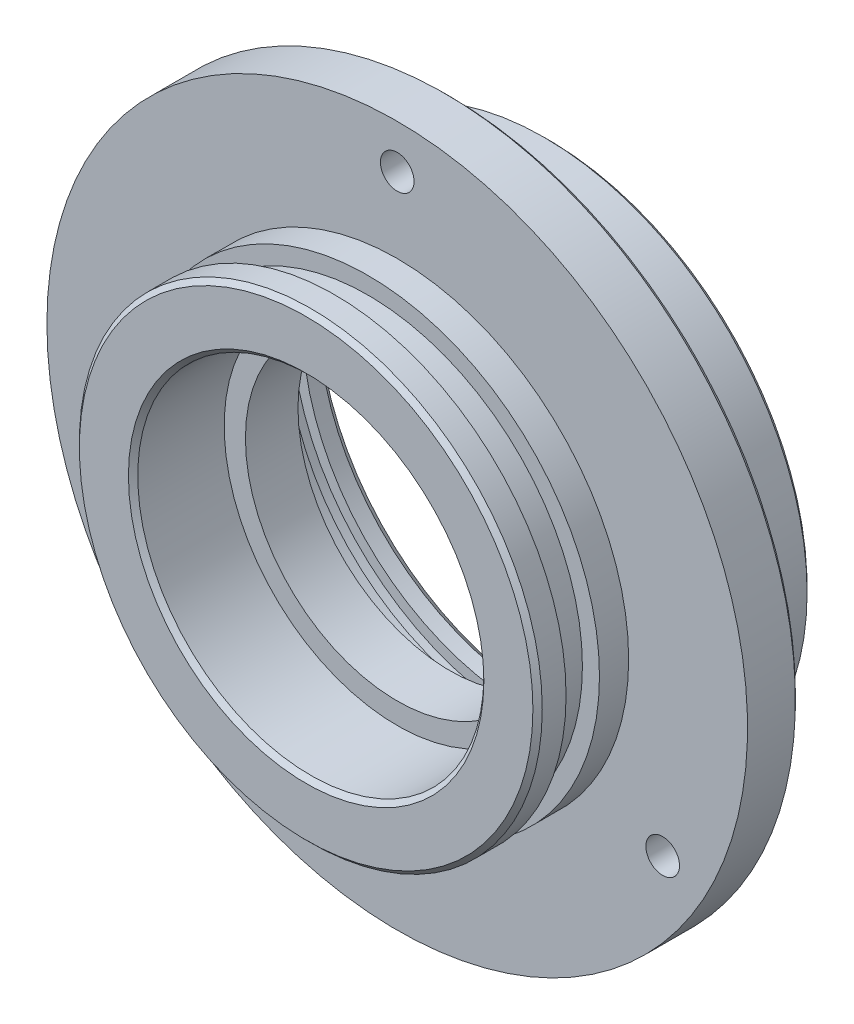
SolidWorks part; units mm, degrees
material "6061-T6 (SS)"
ref_plane "Front Plane" through (0, 0, 0) normal (0, 0, 1) x (1, 0, 0)
ref_plane "Top Plane" through (0, 0, 0) normal (0, 1, 0) x (1, 0, 0)
ref_plane "Right Plane" through (0, 0, 0) normal (1, 0, 0) x (0, 0, -1)
sketch "Sketch1" plane through (0, 0, 0) normal (0, 0, 1) x (1, 0, 0)
  circle A0 centre (0, 0) radius 25.1714
  circle A1 centre (0, 0) radius 18.8214
  dimension "D1" = 50.3428
  dimension "D2" = 6.35
extrude "Boss-Extrude1" add sketch "Sketch1" against normal blind 9.906
sketch "Sketch2" plane through (0, 0, -9.906) normal (0, 0, -1) x (-1, 0, 0)
  circle A0 centre (0, 0) radius 28.575
  dimension "D1" = 57.15
extrude "Boss-Extrude2" add sketch "Sketch2" along normal blind 5.08
ref_plane "Plane1" through (0, 0, -6.731) normal (0, 0, 1) x (1, 0, 0)
sketch "Sketch3" plane through (0, 0, -6.731) normal (0, 0, 1) x (1, 0, 0)
  circle A0 centre (0, 0) radius 25.1714
  circle A1 centre (0, 0) radius 25.1714 construction
  circle A2 centre (0, 0) radius 23.3172
  dimension "D1" = 46.6344
extrude "Cut-Extrude1" cut sketch "Sketch3" along normal blind 3.6322
ref_axis "Axis1" through (0, 0, -23.6329) along (0, 0, 1)
sketch "Sketch4" plane through (0, 0, 0) normal (1, 0, 0) x (0, 0, -1)
  line L0 (9.906, 16.51) -> (9.906, 28.575)
  line L1 (9.906, 28.575) -> (26.416, 28.575)
  line L2 (26.416, 28.575) -> (26.416, 24.0665)
  line L3 (26.416, 24.0665) -> (15.621, 24.0665)
  line L4 (9.906, 28.575) -> (9.906, -28.575) construction
  line L8 (15.621, 24.0665) -> (15.621, 16.51)
  line L9 (15.621, 16.51) -> (9.906, 16.51)
  line L12 (0, 0) -> (50000, 0) construction
  dimension "D2" = 5.715
  dimension "D5" = 57.15
  dimension "D6" = 48.133
  dimension "D8" = 33.02
  dimension "D9" = 10.795
revolve "Revolve1" add sketch "Sketch4" angle 360 about axis through (0, 0, -23.6329) along (0, 0, 1)
sketch "Sketch5" plane through (0, 0, 0) normal (1, 0, 0) x (0, 0, -1)
  line L0 (23.6329, 0) -> (2.6761, 0) construction
  line L1 (21.8948, 25.2603) -> (23.6728, 25.2603)
  line L2 (21.8948, 25.2603) -> (21.8948, 12.7)
  line L3 (21.8948, 12.7) -> (23.6728, 12.7)
  line L4 (23.6728, 25.2603) -> (23.6728, 12.7)
  dimension "D1" = 1.778
  dimension "D2" = 25.2603
  dimension "D3" = 12.7
  dimension "D4" = 6.2738
revolve "Cut-Revolve1" cut sketch "Sketch5" angle 360 about axis through (0, 0, -23.6329) along (0, 0, 1)
sketch "Sketch6" plane through (0, 0, -14.986) normal (0, 0, -1) x (-1, 0, 0)
  circle A0 centre (0, 0) radius 16.51
  circle A1 centre (0, 0) radius 16.51 construction
extrude "Cut-Extrude2" cut sketch "Sketch6" against normal through all
sketch "Sketch7" plane through (0, 0, -15.621) normal (0, 0, -1) x (-1, 0, 0)
  circle A1 centre (0, 0) radius 28.575 construction
  circle A2 centre (0, 0) radius 38.1
  circle A4 centre (0, 0) radius 38.1
  circle A5 centre (0, 0) radius 28.575
  dimension "D1" = 9.525
sketch "Sketch10" plane through (0, 0, 0) normal (1, 0, 0) x (0, 0, -1)
  line L0 (0, 0) -> (50000, 0) construction
  line L1 (13.7414, 23.1775) -> (15.621, 23.1775)
  line L2 (13.7414, 23.1775) -> (13.7414, 19.6723)
  line L3 (13.7414, 19.6723) -> (15.621, 19.6723)
  line L4 (15.621, 23.1775) -> (15.621, 19.6723)
  line L5 (15.621, -16.51) -> (15.621, 16.51) construction
  dimension "D1" = 1.8796
  dimension "D2" = 3.5052
  dimension "D3" = 39.3446
revolve "Cut-Revolve2" cut sketch "Sketch10" angle 360 about L0
extrude "Boss-Extrude3" add sketch "Sketch7" against normal up to surface (5.715 mm away) up to face at (-25.1714, 0, -9.906)
hole_wizard "#6 Clearance Hole1" positions "Sketch9" profile "Sketch8" hole size "#6" standard "ANSI Inch" end condition through all
sketch "Sketch9" plane through (12.684, 15.4202, -15.621) normal (0, 0, -1) x (-1, 0, 0)
  line L1 (12.684, 22.6798) -> (12.684, 13.1548)
  circle A0 centre (12.684, -15.4202) radius 38.1 construction
  circle A1 centre (12.684, -15.4202) radius 28.575 construction
  point P26 (12.684, 17.9173)
sketch "Sketch8" plane through (0, 33.3375, -15.621) normal (1, 0, 0) x (0, 1, 0)
  line L0 (0, 0) -> (0, 15.621)
  line L1 (0, 15.621) -> (1.8288, 15.621)
  line L2 (1.8288, 15.621) -> (1.8288, 0)
  line L5 (1.8288, 0) -> (0, 0)
  line L11 (0, -6.35) -> (0, 107.95) construction
  dimension "Thru Hole Dia." = 3.6576
  dimension "Thru Hole Depth" = 15.621
pattern_circular "CirPattern1" count 3 over 360 about axis through (0, 0, 0) along (0, 0, 1) of "#6 Clearance Hole1"
chamfer "Chamfer1" distance 0.508 angle 45 4 edges at (25.1714, 0, 0) (18.8214, 0, 0) (-28.575, 0, -26.416) (-38.1, 0, -15.621)
chamfer "Chamfer3" distance 1.016 angle 45 1 edges at (-24.0665, 0, -26.416)
